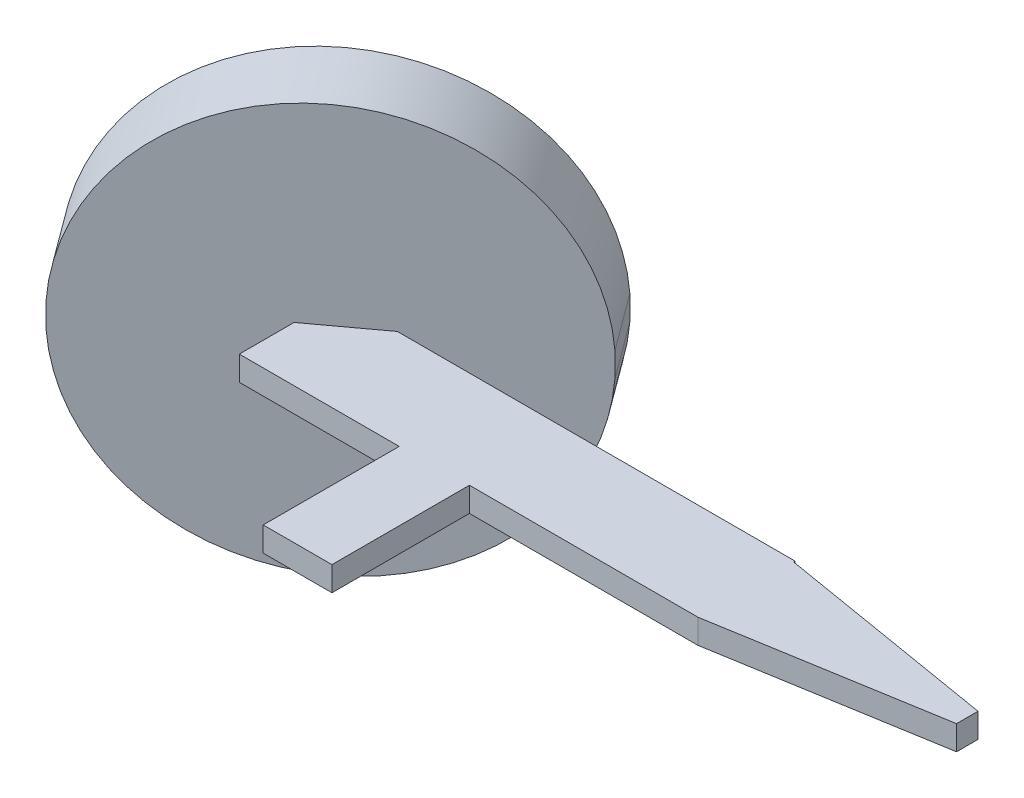
SolidWorks part; units mm, degrees
ref_plane "Front Plane" through (0, 0, 0) normal (0, 0, 1) x (1, 0, 0)
ref_plane "Top Plane" through (0, 0, 0) normal (0, 1, 0) x (1, 0, 0)
ref_plane "Right Plane" through (0, 0, 0) normal (1, 0, 0) x (0, 0, -1)
sketch "Sketch1" plane through (0, 0, 0) normal (0, 1, 0) x (1, 0, 0)
  line L0 (-55.2233, -1.1646) -> (-62.0773, 8.1372)
  line L2 (-5.63, 7.0988) -> (-5.63, -15.1766)
  line L3 (-5.63, -15.1766) -> (5.63, -15.1766)
  line L4 (5.63, 7.3435) -> (5.63, -15.1766)
  line L7 (-31.822, 7.0988) -> (-5.63, 7.0988)
  line L8 (-31.822, 7.0988) -> (-31.822, 16.0785)
  line L9 (-22.0831, 23.2545) -> (43.0821, 23.2545)
  line L10 (43.0821, 7.0988) -> (43.0821, 7.3435)
  line L12 (41.9472, 23.0098) -> (43.0821, 23.2545) construction
  line L13 (-55.2233, -1.1646) -> (-31.822, 16.0785)
  line L14 (-62.0773, 8.1372) -> (-8.4207, 47.6737)
  line L15 (-1.5667, 38.3719) -> (-8.4207, 47.6737)
  line L20 (89.8359, 7.3435) -> (89.8359, 23.0098)
  line L21 (-3.6718, 23.0098) -> (89.8359, 23.0098)
  line L23 (-22.0831, 23.2545) -> (-1.5667, 38.3719)
  line L25 (5.63, 7.0988) -> (43.0821, 7.0988)
  line L26 (5.63, 7.3435) -> (89.8359, 7.3435)
  line L29 (41.9472, 7.3435) -> (43.0821, 7.0988) construction
  line L31 (43.0821, 23.0098) -> (43.0821, 23.2545)
  point P0 (0, 0)
  point P11 (43.0821, 15.1766)
extrude "Boss-Extrude2" add sketch "Sketch1" against normal blind 4
sketch "Sketch2" plane through (-25.7301, 0, -34.9194) normal (-0.5932, 0, -0.8051) x (-0.8051, 0, 0.5932)
  line L4 (45.1487, 0) -> (-21.5009, 0)
  line L5 (-21.5009, 0) -> (-21.5009, -4)
  line L6 (-21.5009, -4) -> (45.1487, -4)
  line L7 (45.1487, -4) -> (45.1487, 0)
  line L9 (-21.5009, 0) -> (-21.5009, -4)
  line L11 (45.1487, -4) -> (45.1487, 0)
  circle A0 centre (11.8239, -2) radius 33.3847
  point P9 (11.8239, -2)
  line M1 (45.1487, 0) -> (-21.5009, 0)
  line M2 (-21.5009, 0) -> (-21.5009, -4)
  line M3 (-21.5009, -4) -> (45.1487, -4)
  line M4 (45.1487, -4) -> (45.1487, 0)
  dimension "D1" = 0
extrude "Boss-Extrude3" add sketch "Sketch2" against normal up to surface (11.5542 mm away) contours A0 M1 | M4 M1 M2 M3 | A0 M3 up to face at (-11.8249, -2, -30.8132)
sketch "Sketch3" plane through (0, -4, 0) normal (0, -1, 0) x (1, 0, 0)
  line L0 (79.346, -16.9341) -> (43.0821, -23.0098)
  line L1 (79.346, -13.4192) -> (43.0821, -7.3435)
  line L2 (89.8359, -23.0098) -> (89.8359, -7.3435)
  line L3 (89.8359, -23.0098) -> (79.346, -23.0098)
  line L4 (89.8359, -7.3435) -> (79.346, -7.3435)
  line L5 (79.346, -16.9341) -> (79.346, -13.4192)
  line L11 (-31.822, -7.0988) -> (-31.822, -16.0785)
  line L12 (-31.822, -16.0785) -> (-22.0831, -23.2545)
  line L13 (-22.0831, -23.2545) -> (43.0821, -23.2545)
  line L14 (43.0821, -23.2545) -> (43.0821, -23.0098)
  line L15 (43.0821, -23.0098) -> (89.8359, -23.0098)
  line L16 (89.8359, -23.0098) -> (89.8359, -7.3435)
  line L17 (89.8359, -7.3435) -> (5.63, -7.3435)
  line L18 (5.63, -7.3435) -> (5.63, 15.1766)
  line L19 (5.63, 15.1766) -> (-5.63, 15.1766)
  line L20 (-5.63, 15.1766) -> (-5.63, -7.0988)
  line L21 (-5.63, -7.0988) -> (-31.822, -7.0988)
  line L22 (-31.822, -7.0988) -> (-31.822, -16.0785)
  line L23 (-31.822, -16.0785) -> (-22.0831, -23.2545)
  line L24 (-22.0831, -23.2545) -> (43.0821, -23.2545)
  line L25 (43.0821, -23.2545) -> (43.0821, -23.0098)
  line L26 (43.0821, -23.0098) -> (89.8359, -23.0098)
  line L27 (89.8359, -23.0098) -> (89.8359, -7.3435)
  line L28 (89.8359, -7.3435) -> (5.63, -7.3435)
  line L29 (5.63, -7.3435) -> (5.63, 15.1766)
  line L30 (5.63, 15.1766) -> (-5.63, 15.1766)
  line L31 (-5.63, 15.1766) -> (-5.63, -7.0988)
  line L32 (-5.63, -7.0988) -> (-31.822, -7.0988)
  line M16 (43.0821, -23.0098) -> (89.8359, -23.0098)
  line M17 (89.8359, -23.0098) -> (89.8359, -7.3435)
  line M18 (89.8359, -7.3435) -> (5.63, -7.3435)
  dimension "D1" = 0
extrude "Cut-Extrude1" cut sketch "Sketch3" against normal blind 15 contours L5 L0 L1 M16 M17 M18
